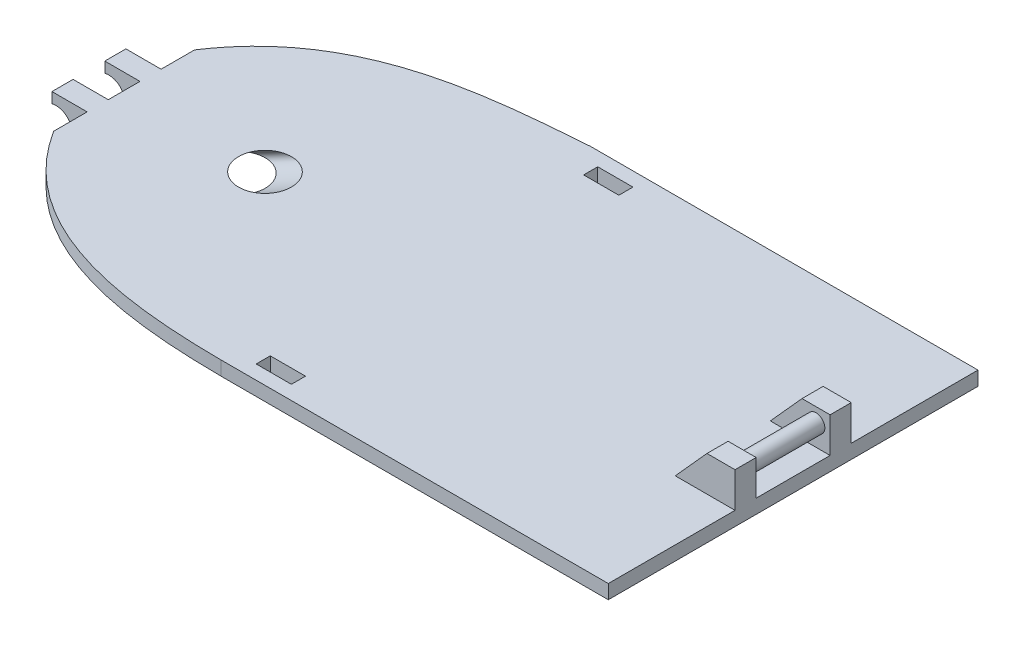
SolidWorks part; units mm, degrees
ref_plane "Front Plane" through (0, 0, 0) normal (0, 0, 1) x (1, 0, 0)
ref_plane "Top Plane" through (0, 0, 0) normal (0, 1, 0) x (1, 0, 0)
ref_plane "Right Plane" through (0, 0, 0) normal (1, 0, 0) x (0, 0, -1)
sketch "Sketch1" plane through (0, 0, 0) normal (0, 1, 0) x (1, 0, 0)
  line L0 (-110, 0) -> (0, 0)
  line L1 (0, 0) -> (0, -105)
  line L2 (0, -105) -> (-110, -105)
  line L4 (-190, -72.5) -> (-190, -32.5)
  spline S0 degree 3 poles (-190, -32.5) (-171.7074, -4.6189) (-138.9899, -2.1787) (-110, 0) knots 0 0 0 0 1 1 1 1
  spline S1 degree 2 poles (-190.0397, -35.2371) (-187.6331, -30.2964) (-183.9056, -25.9107) (-180.479, -21.8792) (-175.9528, -18.3354) (-171.8462, -15.1201) (-166.8566, -12.3231) (-164.564, -11.0379) (-162.0905, -9.8442) (-159.6124, -8.6482) (-157.2765, -7.6915) knots 0 0 0 0.25 0.25 0.5 0.5 0.75 0.75 0.875 0.875 1 1 1 construction
  spline S2 degree 2 poles (-157.2765, -7.6915) (-155.8569, -7.11) (-154.4721, -6.6099) (-153.0466, -6.0951) (-151.6197, -5.6536) (-148.8172, -4.7863) (-145.7427, -4.1123) (-142.8487, -3.4777) (-139.6519, -3.0009) (-136.688, -2.5589) (-133.369, -2.2385) knots 0 0 0 0.125 0.125 0.25 0.25 0.5 0.5 0.75 0.75 1 1 1 construction
  spline S3 degree 3 poles (-190, -72.5) (-172.2628, -100.7004) (-139.266, -104.8361) (-110, -105) knots 0 0 0 0 1 1 1 1
  point P11 (-190, -52.5)
  point P12 (0, -52.5)
  dimension "D4" = 40
  dimension "D1" = 110
  dimension "D2" = 105
  dimension "D3" = 190
  dimension "D5" = 110
extrude "Boss-Extrude1" add sketch "Sketch1" along normal blind 4
sketch "Sketch2" plane through (0, 0, 105) normal (0, 0, 1) x (1, 0, 0)
  line L0 (-190, 4) -> (-200, 4)
  line L1 (-178, 0) -> (-190, -11)
  line L2 (57.75, 0) -> (-57.75, 0) construction
  line L3 (-190, -11) -> (-200, -11)
  line L4 (-200, 4) -> (-200, 1)
  line L5 (-200, -11) -> (-200, -8)
  line L6 (-190, 4) -> (-178, 0)
  arc A0 (-200, 1) -> (-200, -8) centre (-198.8457, -3.5) cw
  point P11 (-194.2, -3.5)
  dimension "D8" = 4.6457
  dimension "D1" = 10
  dimension "D2" = 15
  dimension "D3" = 3
  dimension "D4" = 3
  dimension "D5" = 10
  dimension "D6" = 5.8
  dimension "D7" = 22
extrude "Boss-Extrude2" add sketch "Sketch2" along normal mid plane 6 from offset 45 offset against normal yes
ref_plane "Plane1" through (0, 0, 52.5) normal (0, 0, 1) x (1, 0, 0)
mirror "Mirror1" about plane through (0, 0, 52.5) normal (0, 0, 1) of "Boss-Extrude2"
ref_plane "Plane2" through (-100, 0, 0) normal (1, 0, 0) x (0, 0, -1)
sketch "Sketch5" plane through (0, 0, 105) normal (0, 0, 1) x (1, 0, 0)
  line L0 (-16.9798, 4) -> (-7.9798, 14)
  line L1 (-110, 4) -> (0, 4) construction
  line L2 (-7.9798, 14) -> (0, 14)
  line L3 (0, 14) -> (0, 4)
  line L4 (0, 4) -> (-16.9798, 4)
  dimension "D1" = 10
  dimension "D2" = 9
extrude "Boss-Extrude3" add sketch "Sketch5" along direction (0, 0, 1) on the side against the normal mid plane 6 from offset 39 contours L2 L3 L4 L0 offset against normal yes
mirror "Mirror4" about plane through (0, 0, 52.5) normal (0, 0, 1) of "Boss-Extrude3"
sketch "Sketch6" plane through (0, 0, 42) normal (0, 0, 1) x (1, 0, 0)
  line L0 (0, -13.75) -> (0, 13.75) construction
  line L1 (-110, 4) -> (0, 4) construction
  circle A0 centre (-4, 10) radius 2.5
  dimension "D1" = 5
  dimension "D2" = 4
  dimension "D3" = 6
extrude "Boss-Extrude4" add sketch "Sketch6" along normal up to body separate body
sketch "Sketch7" plane through (0, 4, 0) normal (0, 1, 0) x (1, 0, 0)
  line L0 (-110, -105) -> (0, -105) construction
  line L1 (-104, -101) -> (-94, -101)
  line L2 (-104, -101) -> (-104, -97)
  line L3 (-104, -97) -> (-94, -97)
  line L4 (-94, -101) -> (-94, -97)
  dimension "D1" = 6
  dimension "D2" = 10
  dimension "D3" = 4
  dimension "D4" = 4
extrude "Cut-Extrude1" cut sketch "Sketch7" against normal blind 10
mirror "Mirror5" about plane through (0, 0, 52.5) normal (0, 0, 1) of "Cut-Extrude1"
sketch "Sketch8" plane through (0, 4, 0) normal (0, 1, 0) x (1, 0, 0)
  line L0 (-13.75, -52.5) -> (13.75, -52.5) construction
  line L1 (-190, -48) -> (-190, -57) construction
  circle A0 centre (-150, -52.5) radius 7.5
  dimension "D2" = 15
  dimension "D1" = 40
sketch "Sketch9" plane through (0, 0, 52.5) normal (0, 0, 1) x (1, 0, 0)
  line L0 (-150, 4) -> (-163.8674, -3.4662)
  line L1 (-142.5, 4) -> (-157.5, 4) construction
sweep "Cut-Sweep1" cut profiles "Sketch8" path "Sketch9"
